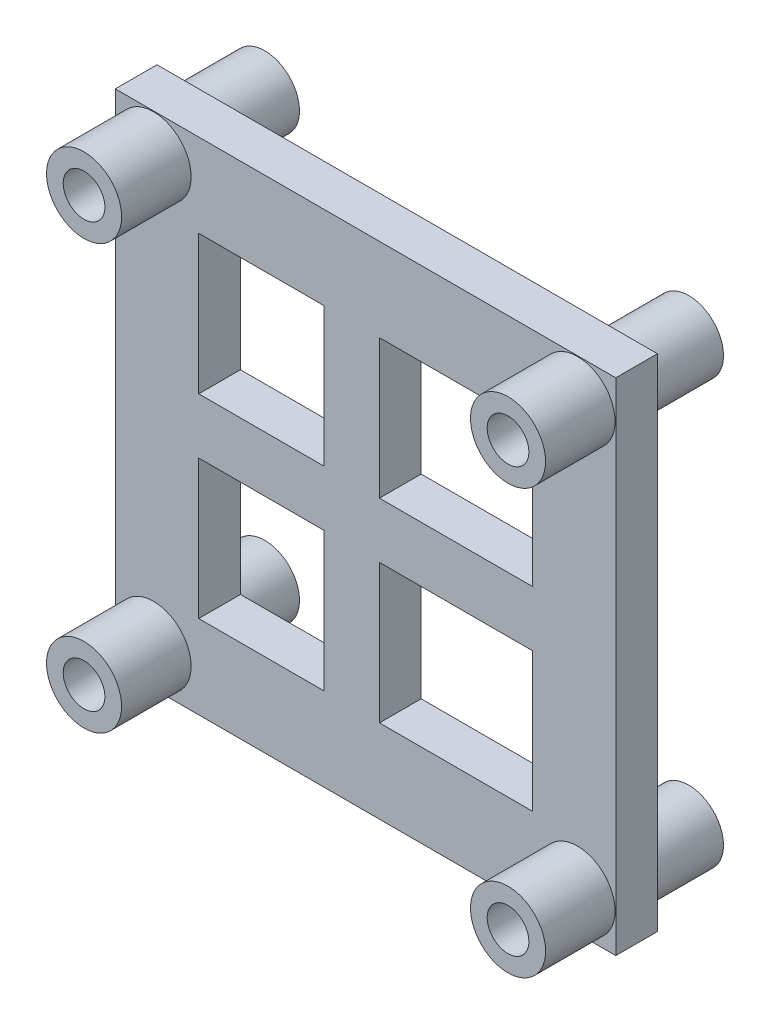
SolidWorks part; units mm, degrees
ref_plane "Alzado" through (0, 0, 0) normal (0, 0, 1) x (1, 0, 0)
ref_plane "Planta" through (0, 0, 0) normal (0, 1, 0) x (1, 0, 0)
ref_plane "Vista lateral" through (0, 0, 0) normal (1, 0, 0) x (0, 0, -1)
sketch "Croquis1" plane through (0, 0, 0) normal (0, 0, 1) x (1, 0, 0)
  line L1 (-42.8938, 20.2642) -> (-6.8938, 20.2642)
  line L2 (-42.8938, 20.2642) -> (-42.8938, -15.7358)
  line L3 (-42.8938, -15.7358) -> (-6.8938, -15.7358)
  line L4 (-6.8938, 20.2642) -> (-6.8938, -15.7358)
  dimension "D1" = 36
  dimension "D2" = 36
extrude "Saliente-Extruir1" add sketch "Croquis1" along normal blind 13
sketch "Croquis5" plane through (0, 0, 0) normal (0, 0, -1) x (-1, 0, 0)
  line L0 (42.8938, 20.2642) -> (42.8938, -15.7358) construction
  line L1 (6.8938, 20.2642) -> (42.8938, 20.2642) construction
  circle A0 centre (40.1438, 17.5142) radius 1.5
  circle A1 centre (40.1438, -12.9858) radius 1.5
  circle A2 centre (9.6438, -12.9858) radius 1.5
  circle A3 centre (9.6438, 17.5142) radius 1.5
  dimension "D1" = 30.5
  dimension "D2" = 30.5
  dimension "D3" = 30.5
  dimension "D4" = 30.5
  dimension "D5" = 2.75
  dimension "D6" = 2.75
  dimension "D7" = 2.75
  dimension "D8" = 2.75
extrude "Cortar-Extruir2" cut sketch "Croquis5" against normal up to vertex (13 mm away)
sketch "Croquis6" plane through (0, 0, 0) normal (0, 0, -1) x (-1, 0, 0)
  line L0 (42.8938, 20.2642) -> (6.8938, 20.2642)
  line L1 (6.8938, 20.2642) -> (6.8938, -15.7358)
  line L2 (6.8938, -15.7358) -> (42.8938, -15.7358)
  line L3 (42.8938, -15.7358) -> (42.8938, 20.2642)
  circle A0 centre (40.1438, 17.5142) radius 2.5
  circle A1 centre (9.6438, 17.5142) radius 2.5
  circle A2 centre (40.1438, -12.9858) radius 2.5
  circle A3 centre (9.6438, -12.9858) radius 2.5
extrude "Cortar-Extruir3" cut sketch "Croquis6" against normal blind 5
sketch "Croquis7" plane through (0, 0, 13) normal (0, 0, 1) x (1, 0, 0)
  line L0 (-6.8938, 20.2642) -> (-42.8938, 20.2642)
  line L1 (-42.8938, 20.2642) -> (-42.8938, -15.7358)
  line L2 (-42.8938, -15.7358) -> (-6.8938, -15.7358)
  line L3 (-6.8938, -15.7358) -> (-6.8938, 20.2642)
  circle A0 centre (-40.1438, 17.5142) radius 2.7
  circle A1 centre (-9.6438, 17.5142) radius 2.7
  circle A2 centre (-40.1438, -12.9858) radius 2.7
  circle A3 centre (-9.6438, -12.9858) radius 2.7
extrude "Cortar-Extruir4" cut sketch "Croquis7" against normal blind 5
sketch "Croquis8" plane through (0, 0, 8) normal (0, 0, 1) x (1, 0, 0)
  line L0 (-42.8938, 20.2642) -> (-42.8938, -15.7358) construction
  line L1 (-36.8938, -9.7358) -> (-27.8938, -9.7358)
  line L2 (-36.8938, -9.7358) -> (-36.8938, 0.2642)
  line L3 (-36.8938, 0.2642) -> (-27.8938, 0.2642)
  line L4 (-27.8938, -9.7358) -> (-27.8938, 0.2642)
  line L5 (-36.8938, 4.2642) -> (-27.8938, 4.2642)
  line L6 (-36.8938, 4.2642) -> (-36.8938, 14.2642)
  line L7 (-36.8938, 14.2642) -> (-27.8938, 14.2642)
  line L8 (-27.8938, 4.2642) -> (-27.8938, 14.2642)
  line L9 (-6.8938, 20.2642) -> (-42.8938, 20.2642) construction
  line L10 (-42.8938, -15.7358) -> (-6.8938, -15.7358) construction
  line L11 (-6.8938, -15.7358) -> (-6.8938, 20.2642) construction
  line L12 (-23.8938, -9.7358) -> (-12.8938, -9.7358)
  line L13 (-23.8938, -9.7358) -> (-23.8938, 0.2642)
  line L14 (-23.8938, 0.2642) -> (-12.8938, 0.2642)
  line L15 (-12.8938, -9.7358) -> (-12.8938, 0.2642)
  line L16 (-23.8938, 4.2642) -> (-12.8938, 4.2642)
  line L17 (-23.8938, 4.2642) -> (-23.8938, 14.2642)
  line L18 (-23.8938, 14.2642) -> (-12.8938, 14.2642)
  line L19 (-12.8938, 4.2642) -> (-12.8938, 14.2642)
  dimension "D1" = 6
  dimension "D2" = 6
  dimension "D3" = 6
  dimension "D4" = 6
  dimension "D5" = 4
  dimension "D6" = 4
  dimension "D7" = 4
  dimension "D8" = 6
  dimension "D9" = 6
  dimension "D10" = 6
  dimension "D11" = 10
  dimension "D12" = 10
  dimension "D13" = 10
  dimension "D14" = 9
  dimension "D15" = 9
extrude "Cortar-Extruir5" cut sketch "Croquis8" against normal up to vertex (3 mm away)
